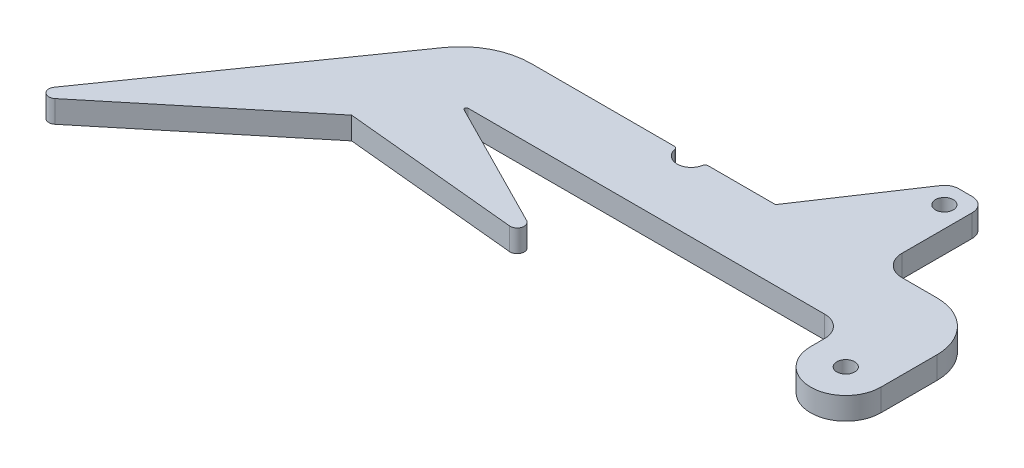
SolidWorks part; units mm, degrees
ref_plane "Front Plane" through (0, 0, 0) normal (0, 0, 1) x (1, 0, 0)
ref_plane "Top Plane" through (0, 0, 0) normal (0, 1, 0) x (1, 0, 0)
ref_plane "Right Plane" through (0, 0, 0) normal (1, 0, 0) x (0, 0, -1)
sketch "Sketch1" plane through (0, 0, 0) normal (0, 1, 0) x (1, 0, 0)
  line L0 (-30, 0) -> (-70, 0)
  line L1 (-70, 0) -> (-95.8109, -36.8618)
  line L2 (-94.3562, -38.2075) -> (-71.1947, -19.1407)
  line L4 (-64.7943, -10) -> (-10, -10)
  line L6 (-71.1947, -19.1407) -> (-46.3114, -21.5535)
  line L7 (-45.762, -19.6666) -> (-64.7943, -10)
  line L8 (0, 0) -> (0, -15)
  line L9 (-10, -10) -> (-10, -15)
  line L10 (-15, 0) -> (0, 0)
  line L12 (-30, 0) -> (-20.5937, 14.1094)
  line L13 (-18.9296, 15) -> (-17, 15)
  line L14 (-15, 0) -> (-15, 13)
  arc A0 (-46.3114, -21.5535) -> (-45.762, -19.6666) centre (-46.2149, -20.5582) ccw
  arc A1 (-94.3562, -38.2075) -> (-95.8109, -36.8618) centre (-94.9918, -37.4354) cw
  arc A3 (0, -15) -> (-10, -15) centre (-5, -15) cw
  arc A4 (-15, 13) -> (-17, 15) centre (-17, 13) ccw
  arc A5 (-18.9296, 15) -> (-20.5937, 14.1094) centre (-18.9296, 13) ccw
  point P16 (-5, -20)
  point P25 (-15, 15)
  point P28 (-20, 15)
  dimension "D1" = 1
  dimension "D17" = 2
  dimension "D2" = 10
  dimension "D3" = 70
  dimension "D4" = 125
  dimension "D5" = 45
  dimension "D6" = 135
  dimension "D7" = 25
  dimension "D8" = 10
  dimension "D9" = 10
  dimension "D10" = 30
  dimension "D11" = 10
  dimension "D12" = 20
  dimension "D13" = 5
  dimension "D14" = 15
  dimension "D15" = 15
  dimension "D16" = 5
extrude "Boss-Extrude1" add sketch "Sketch1" along normal blind 3.175
sketch "Sketch2" plane through (0, 3.175, 0) normal (0, 1, 0) x (1, 0, 0)
  line L0 (-17, 15) -> (-18.9296, 15) construction
  circle A1 centre (-5, -15) radius 1.27
  circle A2 centre (-17.9648, 12) radius 1.27
  point P9 (-17.9648, 15)
  dimension "D1" = 2.54
  dimension "D2" = 2.54
  dimension "D3" = 3
extrude "Cut-Extrude1" cut sketch "Sketch2" against normal up to next
sketch "Sketch3" plane through (0, 3.175, 0) normal (0, 1, 0) x (1, 0, 0)
  line L0 (-30, 0) -> (-70, 0) construction
  line L1 (-44, 0) -> (-40, 0)
  line L2 (0, -15) -> (0, 0) construction
  arc A0 (-40, 0) -> (-44, 0) centre (-42, 0) cw
  dimension "D1" = 2
  dimension "D2" = 40
extrude "Cut-Extrude2" cut sketch "Sketch3" against normal through all
fillet "Fillet1" radius 10 1 edges at (-70, 1.5875, 0)
fillet "Fillet2" radius 0.25 1 edges at (-64.7943, 1.5875, 10)
fillet "Fillet3" radius 3 1 edges at (-10, 1.5875, 10)
fillet "Fillet4" radius 0.5 2 edges at (-40, 1.5875, 0) (-44, 1.5875, 0)
fillet "Fillet5" radius 7 1 edges at (0, 1.5875, 0)
fillet "Fillet6" radius 3 1 edges at (-15, 1.5875, 0)
